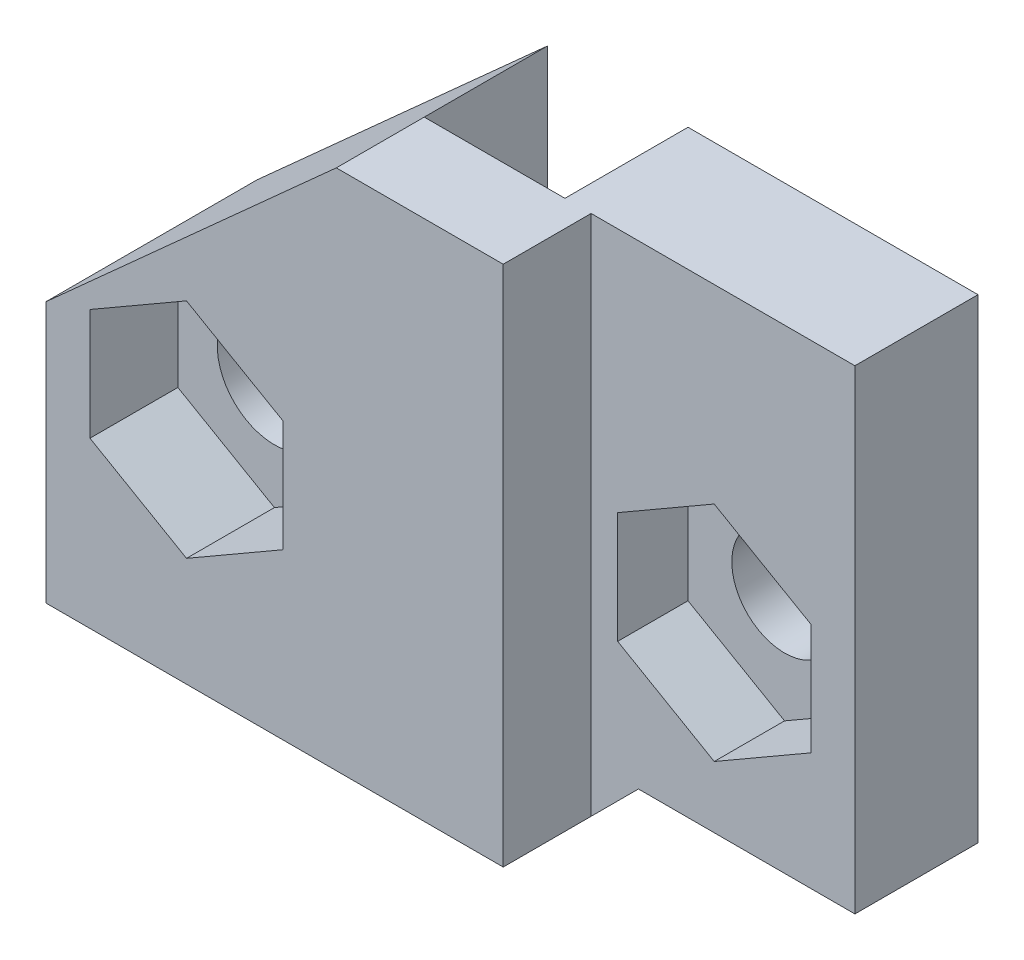
SolidWorks part; units mm, degrees
ref_plane "Alzado" through (0, 0, 0) normal (0, 0, 1) x (1, 0, 0)
ref_plane "Planta" through (0, 0, 0) normal (0, 1, 0) x (1, 0, 0)
ref_plane "Vista lateral" through (0, 0, 0) normal (1, 0, 0) x (0, 0, -1)
sketch "Croquis1" plane through (0, 0, 0) normal (0, 0, 1) x (1, 0, 0)
  line L0 (88.7324, -80.1486) -> (88.7324, -81.4936)
  line L1 (88.7324, -66.6486) -> (96.2324, -66.6486)
  line L2 (88.7324, -66.6486) -> (88.7324, -80.1486)
  line L3 (90.0774, -80.1486) -> (96.2324, -80.1486)
  line L4 (96.2324, -66.6486) -> (96.2324, -80.1486)
  line L5 (88.7324, -81.4936) -> (90.0774, -80.1486)
  circle A0 centre (92.2324, -75.2236) radius 1.5
  dimension "D1" = 3
  dimension "D2" = 90.0774
  dimension "D3" = 96.2324
  dimension "D4" = 80.1486
  dimension "D5" = 81.4936
extrude "Saliente-Extruir1" add sketch "Croquis1" along normal blind 3.5
sketch "Croquis2" plane through (0, 0, 3.5) normal (0, 0, 1) x (1, 0, 0)
  line L0 (88.7324, -66.6486) -> (88.7324, -81.4936) construction
  line L1 (92.2324, -72.0536) -> (89.4871, -73.6386)
  line L2 (89.4871, -73.6386) -> (89.4871, -76.8086)
  line L3 (89.4871, -76.8086) -> (92.2324, -78.3936)
  line L4 (92.2324, -78.3936) -> (94.9777, -76.8086)
  line L5 (94.9777, -76.8086) -> (94.9777, -73.6386)
  line L6 (94.9777, -73.6386) -> (92.2324, -72.0536)
  line L7 (90.0774, -80.1486) -> (96.2324, -80.1486) construction
  circle A0 centre (92.2324, -75.2236) radius 2.7453 construction
  dimension "D1" = 5.4906
  dimension "D2" = 0.7547
  dimension "D3" = 1.755
extrude "Cortar-Extruir1" cut sketch "Croquis2" against normal blind 2
sketch "Croquis3" plane through (0, 0, 3.5) normal (0, 0, 1) x (1, 0, 0)
  line L0 (88.7324, -81.4936) -> (75.7324, -81.4936)
  line L1 (75.7324, -81.4936) -> (75.7324, -74.0711)
  line L2 (75.7324, -74.0711) -> (83.9871, -66.6486)
  line L3 (87.9871, -66.6486) -> (88.7324, -66.6486)
  line L4 (88.7324, -66.6486) -> (88.7324, -81.4936)
  line L5 (83.9871, -66.6486) -> (83.9871, -75.2236)
  line L6 (83.9871, -75.2236) -> (87.9871, -75.2236)
  line L7 (87.9871, -75.2236) -> (87.9871, -66.6486)
  line L9 (89.4871, -73.6386) -> (89.4871, -76.8086) construction
  circle A0 centre (79.7277, -75.2236) radius 1.625
  dimension "D1" = 3.25
  dimension "D2" = 1.5
  dimension "D3" = 5.5
  dimension "D4" = 9.7594
  dimension "D5" = 13.7547
  dimension "D6" = 3.17
  dimension "D7" = 4.3225
  dimension "D8" = 3.1
extrude "Saliente-Extruir2" add sketch "Croquis3" against normal blind 3.5 and the other way blind 2.5
sketch "Croquis4" plane through (0, 0, 6) normal (0, 0, 1) x (1, 0, 0)
  line L0 (88.7324, -81.4936) -> (88.7324, -66.6486) construction
  line L1 (83.9871, -66.6486) -> (87.9871, -66.6486)
  line L2 (83.9871, -66.6486) -> (83.9871, -75.2236)
  line L3 (83.9871, -75.2236) -> (87.9871, -75.2236)
  line L4 (87.9871, -66.6486) -> (87.9871, -75.2236)
  line L5 (88.7324, -66.6486) -> (87.9871, -66.6486) construction
  dimension "D1" = 4.7453
extrude "Saliente-Extruir3" add sketch "Croquis4" against normal blind 2.5
sketch "Croquis5" plane through (0, 0, 6) normal (0, 0, 1) x (1, 0, 0)
  line L1 (79.7277, -78.3936) -> (82.473, -76.8086)
  line L2 (82.473, -76.8086) -> (82.473, -73.6386)
  line L3 (82.473, -73.6386) -> (79.7277, -72.0536)
  line L4 (79.7277, -72.0536) -> (76.9824, -73.6386)
  line L5 (76.9824, -73.6386) -> (76.9824, -76.8086)
  line L6 (76.9824, -76.8086) -> (79.7277, -78.3936)
  circle A0 centre (79.7277, -75.2236) radius 2.7453 construction
  dimension "D1" = 5.4906
extrude "Cortar-Extruir2" cut sketch "Croquis5" against normal blind 2.5
